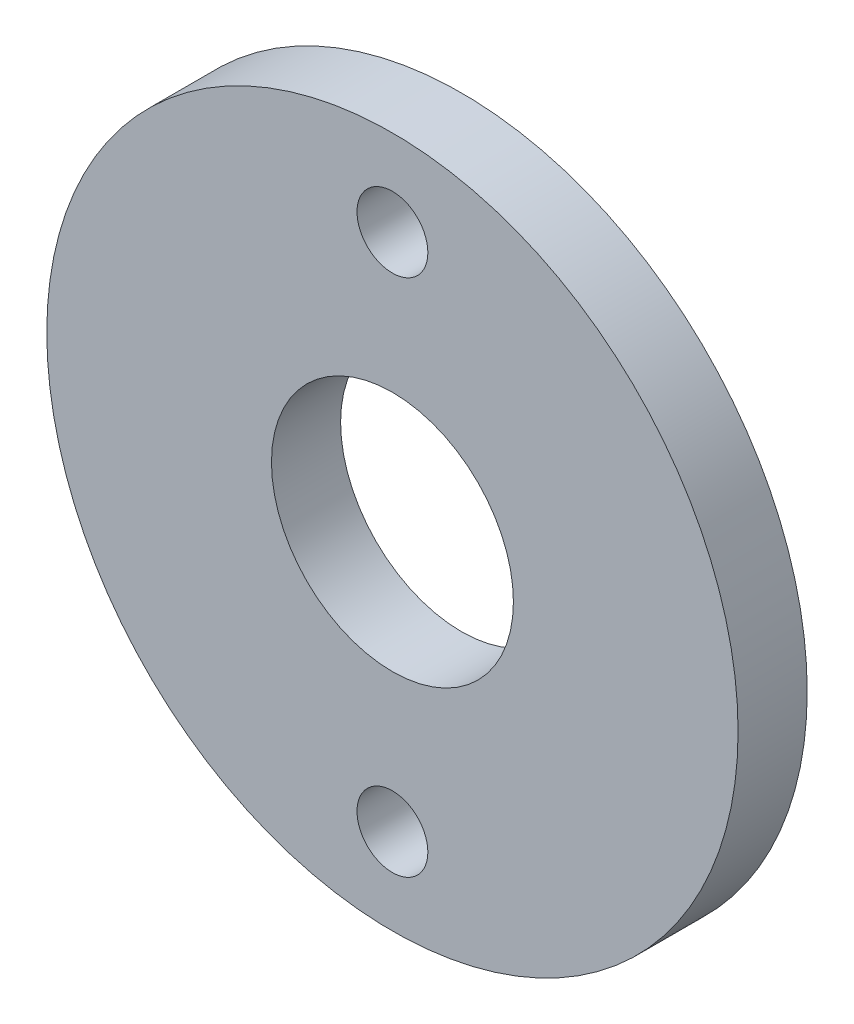
SolidWorks part; units mm, degrees
ref_plane "Alzado" through (0, 0, 0) normal (0, 0, 1) x (1, 0, 0)
ref_plane "Planta" through (0, 0, 0) normal (0, 1, 0) x (1, 0, 0)
ref_plane "Vista lateral" through (0, 0, 0) normal (1, 0, 0) x (0, 0, -1)
sketch "Croquis1" plane through (0, 0, 0) normal (0, 0, 1) x (1, 0, 0)
  circle A0 centre (0, 0) radius 10
  dimension "D1" = 20
extrude "Saliente-Extruir1" add sketch "Croquis1" along normal blind 2
sketch "Croquis2" plane through (0, 0, 2) normal (0, 0, 1) x (1, 0, 0)
  line L0 (0, 10) -> (0, -10) construction
  circle A0 centre (0, 0) radius 10 construction
  circle A1 centre (0, 7.51) radius 1.025
  circle A2 centre (0, -7.51) radius 1.025
  circle A3 centre (0, 0) radius 3.5
  dimension "D1" = 2.05
  dimension "D2" = 2.05
  dimension "D3" = 7.51
  dimension "D4" = 7.51
  dimension "D5" = 7
extrude "Cortar-Extruir1" cut sketch "Croquis2" against normal blind 3
